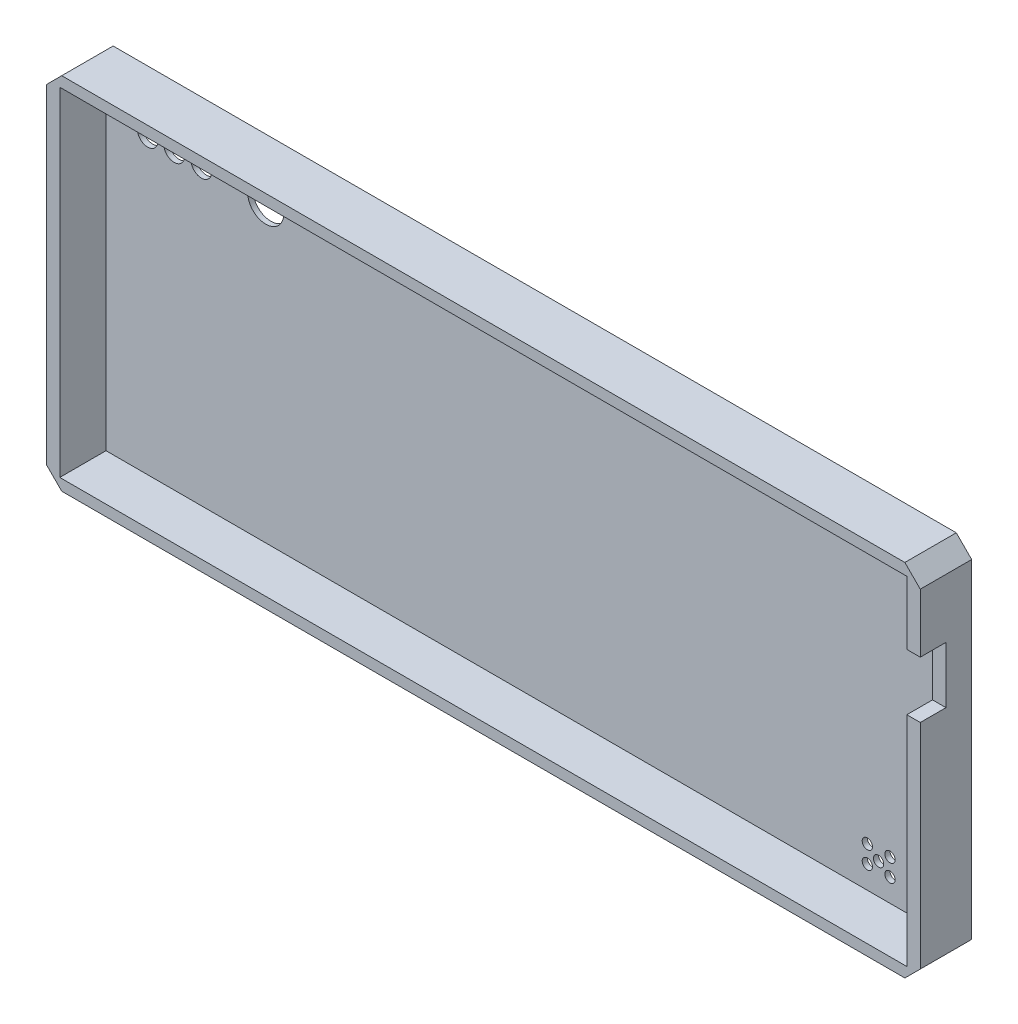
SolidWorks part; units mm, degrees
ref_plane "Front Plane" through (0, 0, 0) normal (0, 0, 1) x (1, 0, 0)
ref_plane "Top Plane" through (0, 0, 0) normal (0, 1, 0) x (1, 0, 0)
ref_plane "Right Plane" through (0, 0, 0) normal (1, 0, 0) x (0, 0, -1)
sketch "Sketch1" plane through (0, 0, 0) normal (0, 0, 1) x (1, 0, 0)
  line L1 (0, 0) -> (170, 0)
  line L2 (0, 0) -> (0, -70)
  line L3 (0, -70) -> (170, -70)
  line L4 (170, 0) -> (170, -70)
extrude "Boss-Extrude1" add sketch "Sketch1" along normal blind 10
sketch "Sketch2" plane through (0, 0, 10) normal (0, 0, 1) x (1, 0, 0)
  line L1 (2.6148, -2.1308) -> (167.3852, -2.1308)
  line L2 (2.6148, -2.1308) -> (2.6148, -67.8692)
  line L3 (2.6148, -67.8692) -> (167.3852, -67.8692)
  line L4 (167.3852, -2.1308) -> (167.3852, -67.8692)
extrude "Cut-Extrude1" cut sketch "Sketch2" against normal blind 9
chamfer "Chamfer1" distance 3 angle 45 4 edges at (170, -70, 5) (170, 0, 5) (0, 0, 5) (0, -70, 5)
sketch "Sketch3" plane through (0, 0, 0) normal (0, 0, -1) x (-1, 0, 0)
  circle A0 centre (-150.7037, -63.4292) radius 1
  circle A1 centre (-155.1034, -63.4292) radius 1
  circle A2 centre (-150.7037, -60.0501) radius 1
  circle A3 centre (-155.1034, -60.0501) radius 1
  circle A4 centre (-152.8834, -61.8816) radius 1
extrude "Cut-Extrude2" cut sketch "Sketch3" against normal blind 9
sketch "Sketch4" plane through (170, 0, 0) normal (1, 0, 0) x (0, 0, -1)
  line L0 (-10, -67) -> (-10, -3) construction
  line L1 (-5, -14.4563) -> (-10, -14.4563)
  line L2 (-5, -14.4563) -> (-5, -25.4563)
  line L3 (-5, -25.4563) -> (-10, -25.4563)
  line L4 (-10, -14.4563) -> (-10, -25.4563)
extrude "Cut-Extrude3" cut sketch "Sketch4" against normal blind 9
sketch "Sketch5" plane through (0, 0, 0) normal (0, 0, -1) x (-1, 0, 0)
  circle A0 centre (-10.7175, -10.6763) radius 2
  circle A1 centre (-15.8657, -10.6763) radius 2
  circle A2 centre (-21.1586, -10.6763) radius 2
  circle A3 centre (-33.6862, -10.6763) radius 3.5
extrude "Cut-Extrude4" cut sketch "Sketch5" against normal blind 9
sketch "Sketch7" plane through (0, 0, 0) normal (0, 0, -1) x (-1, 0, 0)
  text T0 "SM Player" font "Century Gothic" height in points 36
extrude "Boss-Extrude3" add sketch "Sketch7" along normal blind 1
